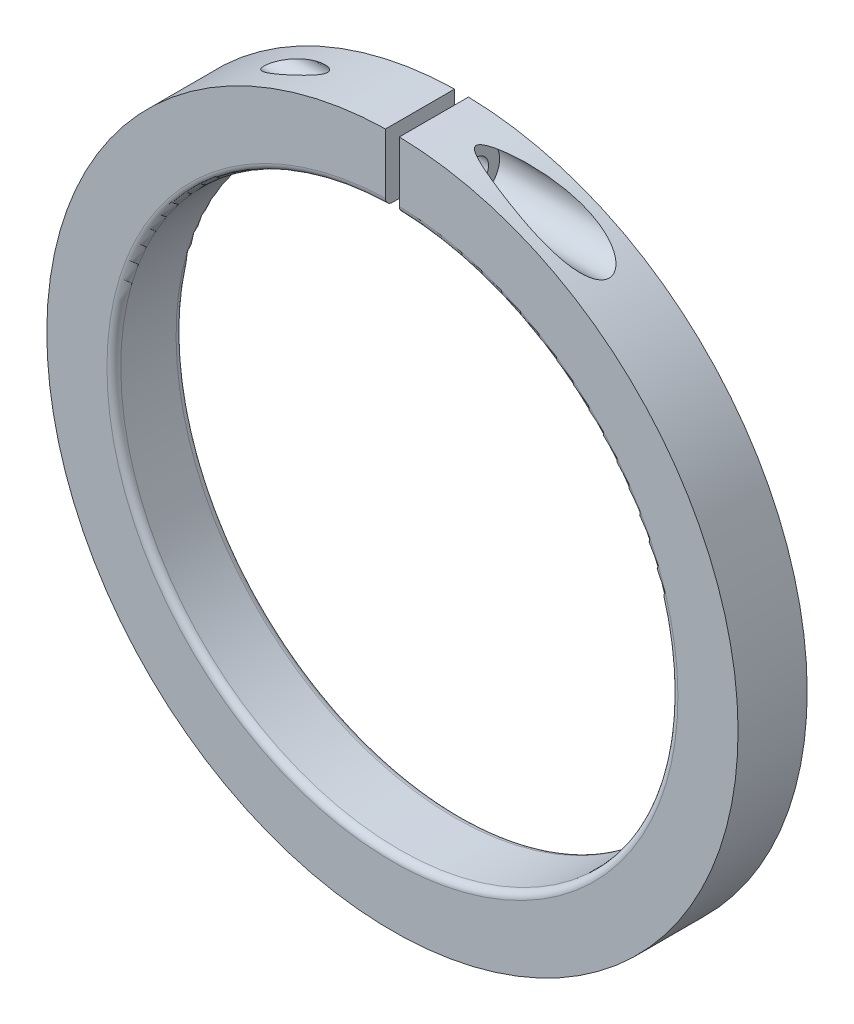
SolidWorks part; units mm, degrees
ref_plane "Front Plane" through (0, 0, 0) normal (0, 0, 1) x (1, 0, 0)
ref_plane "Top Plane" through (0, 0, 0) normal (0, 1, 0) x (1, 0, 0)
ref_plane "Right Plane" through (0, 0, 0) normal (1, 0, 0) x (0, 0, -1)
sketch "Sketch2" plane through (0, 0, 0) normal (0, 0, 1) x (1, 0, 0)
  circle A0 centre (0, 0) radius 25
  circle A1 centre (0, 0) radius 20.15
  dimension "D1" = 50
  dimension "D2" = 40.3
extrude "Boss-Extrude1" add sketch "Sketch2" along normal blind 5
sketch "Sketch3" plane through (0, 0, 5) normal (0, 0, 1) x (1, 0, 0)
  line L0 (-0.5, 0) -> (0.5, 0)
  line L1 (0.5, 0) -> (0.5, 60)
  line L2 (-0.5, 0) -> (-0.5, 60)
  line L3 (-0.5, 60) -> (0.5, 60)
  dimension "D1" = 1
  dimension "D2" = 60
extrude "Cut-Extrude1" cut sketch "Sketch3" against normal blind 5
sketch "Sketch4" plane through (0, 0, 0) normal (1, 0, 0) x (0, 0, -1)
  line L0 (0, 0) -> (-5, -0.0025) construction
  line L1 (-5, 24.995) -> (-5, -25) construction
  line L2 (-2.5, -0.0013) -> (-2.5, 24.995) construction
  line L3 (0, 24.995) -> (-5, 24.995) construction
  circle A0 centre (-2.5, 22.995) radius 0.95
  dimension "D1" = 1.9
  dimension "D2" = 2
extrude "Cut-Extrude2" cut sketch "Sketch4" against normal through all both and the other way through all
sketch "Sketch5" plane through (0, 0, 0) normal (1, 0, 0) x (0, 0, -1)
  circle A0 centre (-2.5, 22.995) radius 1.75
  dimension "D1" = 3.5
ref_plane "Plane1" through (10, 0, 0) normal (1, 0, 0) x (0, 0, -1)
ref_plane "Plane2" through (-10, 0, 0) normal (1, 0, 0) x (0, 0, -1)
sketch "Sketch6" plane through (10, 0, 0) normal (1, 0, 0) x (0, 0, -1)
  circle A0 centre (-2.5, 22.995) radius 1.75
extrude "Cut-Extrude3" cut sketch "Sketch6" against normal blind 6.5 and the other way through all
fillet "Fillet1" radius 0.5 2 edges at (0, -20.15, 0) (0, -20.15, 5)
